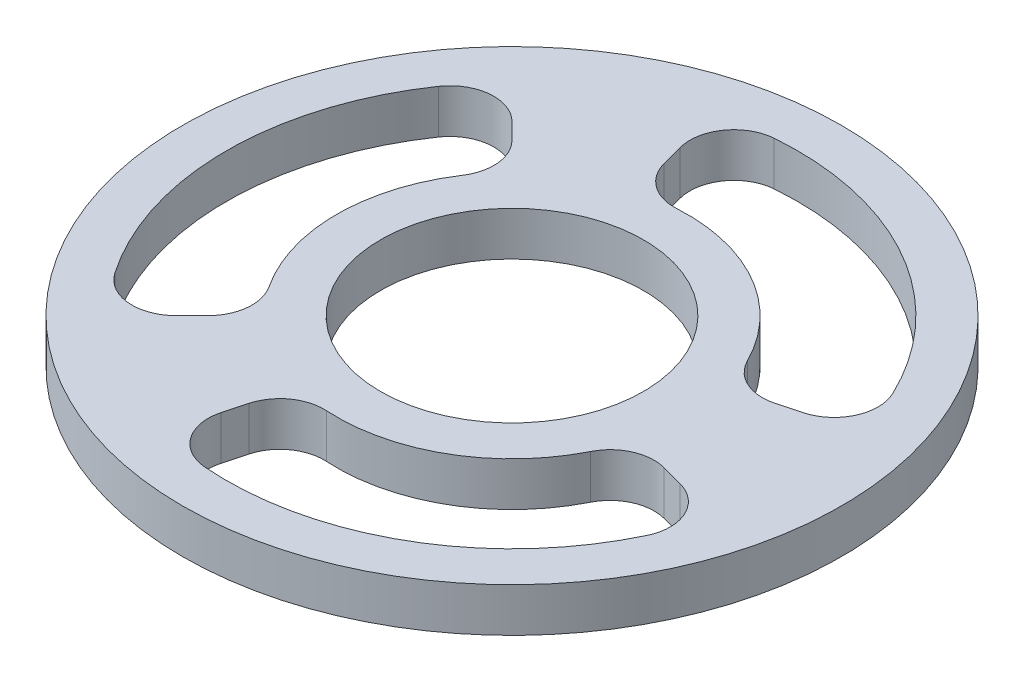
SolidWorks part; units mm, degrees
material "Acrylic (Medium-high impact)"
ref_plane "Front Plane" through (0, 0, 0) normal (0, 0, 1) x (1, 0, 0)
ref_plane "Top Plane" through (0, 0, 0) normal (0, 1, 0) x (1, 0, 0)
ref_plane "Right Plane" through (0, 0, 0) normal (1, 0, 0) x (0, 0, -1)
sketch "Sketch2" plane through (0, 0, 0) normal (0, 1, 0) x (1, 0, 0)
  circle A0 centre (0, 0) radius 47.625
  circle A1 centre (0, 0) radius 19
  dimension "D1" = 95.25
  dimension "D2" = 38
extrude "Boss-Extrude1" add sketch "Sketch2" along normal blind 6.35
sketch "Sketch3" plane through (0, 6.35, 0) normal (0, 1, 0) x (1, 0, 0)
  line L0 (0, 0) -> (74.7241, 0) construction
  line L1 (24.4862, 6.5611) -> (39.8686, 10.6828)
  line L2 (-6.5611, 24.4862) -> (-10.6828, 39.8686)
  line L3 (0, 0) -> (24.4862, 6.5611) construction
  line L4 (0, 0) -> (-6.5611, 24.4862) construction
  arc A0 (24.4862, 6.5611) -> (-6.5611, 24.4862) centre (0, 0) ccw
  arc A1 (39.8686, 10.6828) -> (-10.6828, 39.8686) centre (0, 0) ccw
  circle A2 centre (0, 0) radius 47.625 construction
  circle A3 centre (0, 0) radius 19 construction
  dimension "D1" = 6.35
  dimension "D2" = 6.35
  dimension "D3" = 15
extrude "Cut-Extrude1" cut sketch "Sketch3" against normal through all
fillet "Fillet1" radius 6.35 4 edges at (24.4862, 3.175, -6.5611) (-6.5611, 3.175, -24.4862) (39.8686, 3.175, -10.6828) (-10.6828, 3.175, -39.8686)
pattern_circular "CirPattern1" count 3 every 120 about axis through (0, 0, 0) along (0, 1, 0) of "Cut-Extrude1", "Fillet1"
